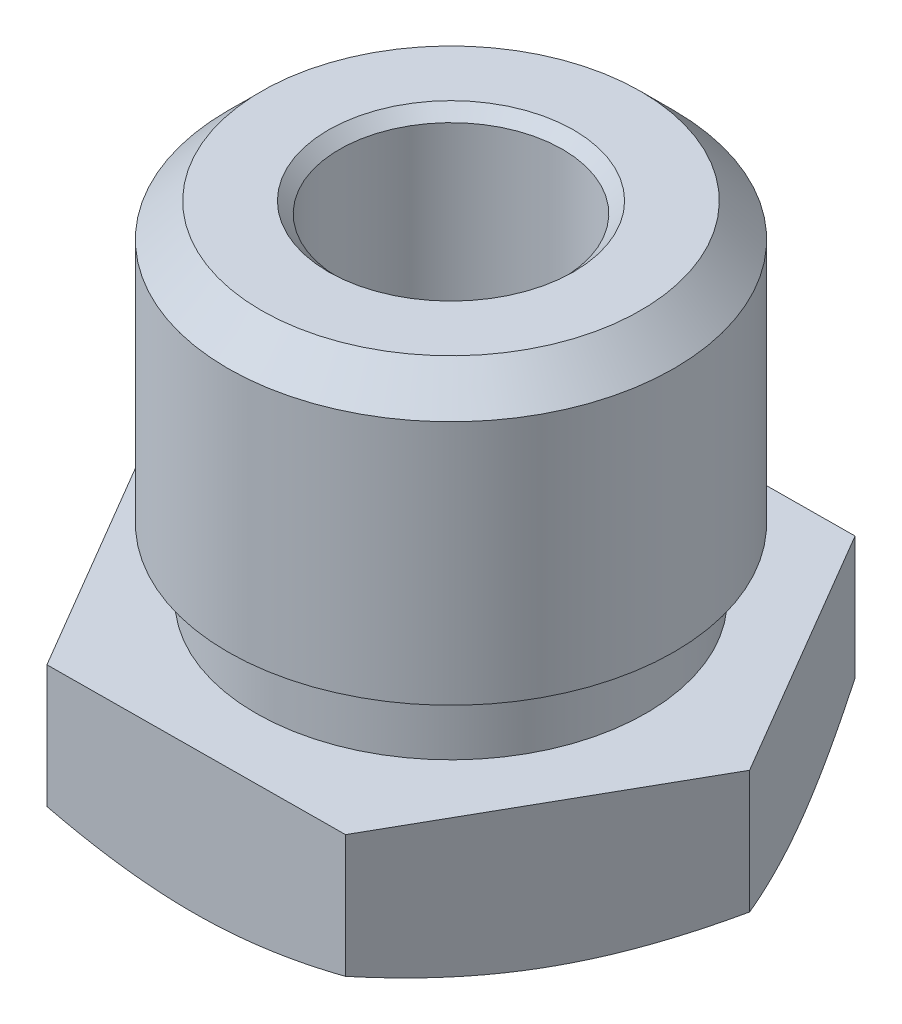
SolidWorks part; units mm, degrees
ref_plane "前视基准面" through (0, 0, 0) normal (0, 0, 1) x (1, 0, 0)
ref_plane "上视基准面" through (0, 0, 0) normal (0, 1, 0) x (1, 0, 0)
ref_plane "右视基准面" through (0, 0, 0) normal (1, 0, 0) x (0, 0, -1)
sketch "草图1" plane through (0, 0, 0) normal (0, 1, 0) x (1, 0, 0)
  line L1 (6.5533, 11.5494) -> (-6.7254, 11.45)
  line L2 (-6.7254, 11.45) -> (-13.2787, -0.0994)
  line L3 (-13.2787, -0.0994) -> (-6.5533, -11.5494)
  line L4 (-6.5533, -11.5494) -> (6.7254, -11.45)
  line L5 (6.7254, -11.45) -> (13.2787, 0.0994)
  line L6 (13.2787, 0.0994) -> (6.5533, 11.5494)
  circle A0 centre (0, 0) radius 11.5 construction
  dimension "D1" = 23
extrude "凸台-拉伸1" add sketch "草图1" along normal blind 6.5
sketch "草图2" plane through (0, 6.5, 0) normal (0, 1, 0) x (1, 0, 0)
  circle A0 centre (0, 0) radius 8.75
extrude "凸台-拉伸2" add sketch "草图2" along normal blind 3
sketch "草图3" plane through (0, 9.5, 0) normal (0, 1, 0) x (1, 0, 0)
  circle A0 centre (0, 0) radius 10
  dimension "D1" = 20
extrude "凸台-拉伸3" add sketch "草图3" along normal blind 12.5 contours A0
cosmetic thread "装饰螺纹线1" parameters "D2"=18.344
chamfer "倒角1" distance 1.5 angle 45 1 edges at (0, 22, 10)
ref_plane "基准面1" through (0, 0, 0) normal (0.8697, 0, 0.4935) x (0.4935, 0, -0.8697)
sketch "草图5" plane through (0, 0, 0) normal (0.8697, 0, 0.4935) x (0.4935, 0, -0.8697)
  line L0 (13.2791, 1) -> (11.2791, 0)
  line L1 (13.2791, 6.5) -> (13.2791, 0) construction
  line L2 (6.6395, 0) -> (13.2791, 0) construction
  line L3 (11.2791, 0) -> (13.2791, 0)
  line L4 (13.2791, 0) -> (13.2791, 1)
  line L5 (0, -1000) -> (0, 49000) construction
  dimension "D1" = 1
  dimension "D2" = 2
revolve "切除-旋转3" cut sketch "草图5" angle 360 about L5
sketch "草图6" plane through (0, 22, 0) normal (0, 1, 0) x (1, 0, 0)
  circle A0 centre (0, 0) radius 5
extrude "切除-拉伸1" cut sketch "草图6" against normal through all
chamfer "倒角2" distance 0.5 angle 45 2 edges at (0, 0, 5) (0, 22, 5)
